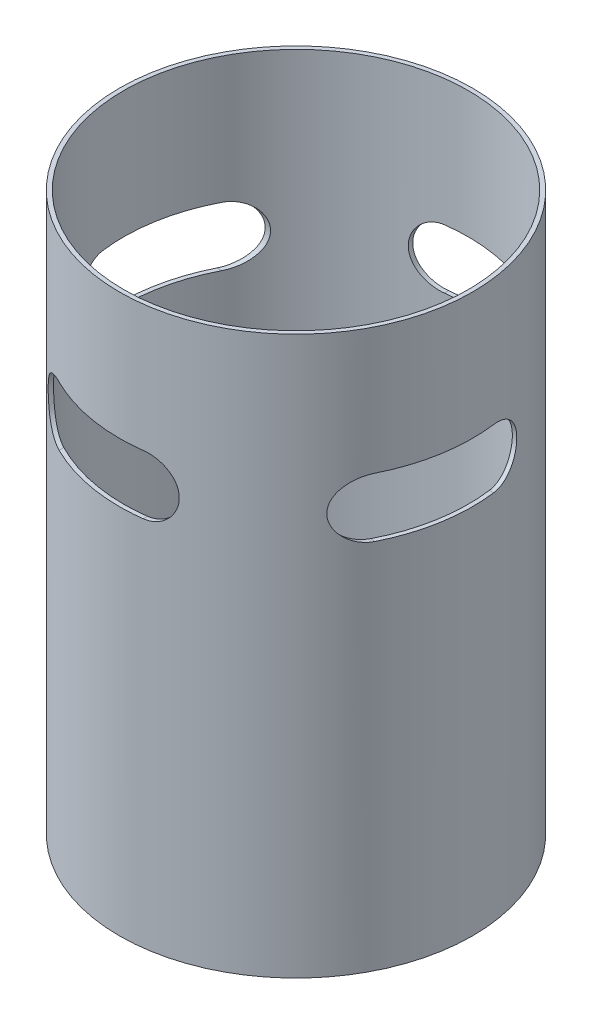
SolidWorks part; units mm, degrees
ref_plane "Front Plane" through (0, 0, 0) normal (0, 0, 1) x (1, 0, 0)
ref_plane "Top Plane" through (0, 0, 0) normal (0, 1, 0) x (1, 0, 0)
ref_plane "Right Plane" through (0, 0, 0) normal (1, 0, 0) x (0, 0, -1)
sketch "Sketch2" plane through (0, 0, 0) normal (0, 1, 0) x (1, 0, 0)
  line L0 (0, -55) -> (0, 55) construction
  line L1 (-55, 0) -> (55, 0) construction
  circle A0 centre (0, 0) radius 20.9
  circle A1 centre (0, 0) radius 20.4
  dimension "D1" = 0.5
  dimension "D2" = 41.8
extrude "Boss-Extrude1" add sketch "Sketch2" along normal blind 66
sketch "Sketch3" plane through (0, 0, 0) normal (0, 1, 0) x (1, 0, 0)
  line L0 (-22.99, 0) -> (22.99, 0) construction
  line L1 (0, -22.99) -> (0, 22.99) construction
  circle A0 centre (0, 0) radius 20.8487
extrude "Boss-Extrude2" add sketch "Sketch3" along normal blind 0.1
sketch "Sketch4" plane through (0, 0, 0) normal (0, 1, 0) x (1, 0, 0)
  line L0 (-22.99, 0) -> (22.99, 0) construction
  circle A0 centre (0.2712, 0) radius 8.6
  dimension "D1" = 17.2
extrude "Boss-Extrude3" add sketch "Sketch4" against normal blind 3.5
sketch "Sketch5" plane through (0, -3.5, 0) normal (0, -1, 0) x (1, 0, 0)
  line L0 (22.99, 0) -> (-22.99, 0) construction
  circle A0 centre (0.3617, 0) radius 2.4
  dimension "D1" = 4.8
extrude "Boss-Extrude4" add sketch "Sketch5" against normal blind 1.35
sketch "Sketch7" plane through (0, -3.5, 0) normal (0, -1, 0) x (1, 0, 0)
  line L0 (22.99, 0) -> (-22.99, 0) construction
  circle A0 centre (0.2712, 0) radius 2.4
  dimension "D1" = 4.8
extrude "Cut-Extrude1" cut sketch "Sketch7" against normal through all
sketch "Sketch8" plane through (0, 0, 0) normal (1, 0, 0) x (0, 0, -1)
  line L0 (-2.8907, 13.6423) -> (9.1093, 13.5831) construction
  line L1 (-2.8734, 17.1423) -> (9.1266, 17.0831)
  line L2 (-2.908, 10.1424) -> (9.092, 10.0832)
  arc A0 (-2.8734, 17.1423) -> (-2.908, 10.1424) centre (-2.8907, 13.6423) ccw
  arc A1 (9.092, 10.0832) -> (9.1266, 17.0831) centre (9.1093, 13.5831) ccw
  point P2 (3.1093, 13.6127)
  dimension "D2" = 12
  dimension "D1" = 7
sketch "Sketch15" plane through (0, 0, 0) normal (1, 0, 0) x (0, 0, -1)
  line L0 (-2.6572, 47.5) -> (9.3428, 47.5) construction
  line L1 (-2.6572, 51) -> (9.3428, 51)
  line L2 (-2.6572, 44) -> (9.3428, 44)
  line L3 (20.9, 66) -> (-20.9, 66) construction
  arc A0 (-2.6572, 51) -> (-2.6572, 44) centre (-2.6572, 47.5) ccw
  arc A1 (9.3428, 44) -> (9.3428, 51) centre (9.3428, 47.5) ccw
  point P2 (3.3428, 47.5)
  dimension "D1" = 15
  dimension "D2" = 7
  dimension "D3" = 12
extrude "Cut-Extrude6" cut sketch "Sketch15" against normal through all contours L2 A1 L1 A0
pattern_circular "CirPattern2" count 4 over 360 about axis through (0, 66, 0) along (0, -1, 0) of "Cut-Extrude6"
